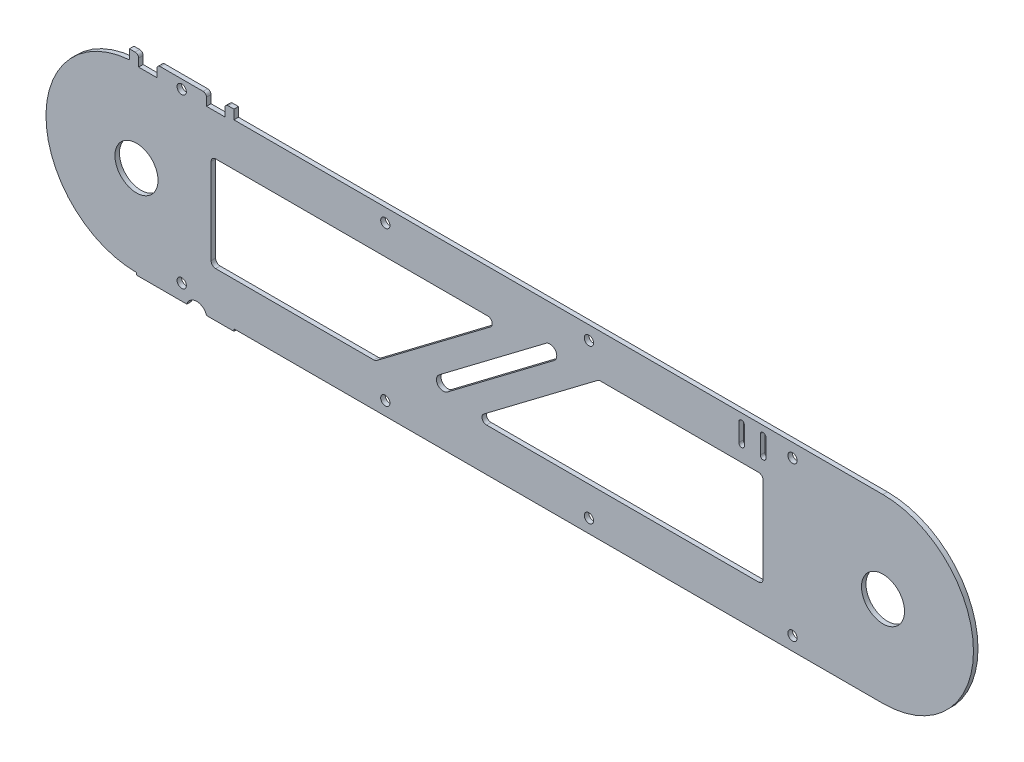
SolidWorks part; units mm, degrees
ref_plane "前视基准面" through (0, 0, 0) normal (0, 0, 1) x (1, 0, 0)
ref_plane "上视基准面" through (0, 0, 0) normal (0, 1, 0) x (1, 0, 0)
ref_plane "右视基准面" through (0, 0, 0) normal (1, 0, 0) x (0, 0, -1)
sketch "草图1" plane through (0, 0, 0) normal (0, 0, 1) x (1, 0, 0)
  line L0 (328.5429, -0.1457) -> (-1.4571, -0.1457) construction
  line L8 (328.5429, -40.1457) -> (-1.4571, -40.1457)
  line L9 (-1.4571, 39.8543) -> (328.5429, 39.8543)
  line L10 (275.5429, 31.8543) -> (266.0429, 31.8543) construction
  line L11 (275.5429, 35.8543) -> (275.5429, 27.8543) construction
  line L12 (276.7929, 35.8543) -> (276.7929, 27.8543)
  line L13 (274.2929, 35.8543) -> (274.2929, 27.8543)
  line L14 (266.0429, 27.8543) -> (266.0429, 35.8543) construction
  line L15 (264.7929, 27.8543) -> (264.7929, 35.8543)
  line L16 (267.2929, 27.8543) -> (267.2929, 35.8543)
  circle A0 centre (-1.4571, -0.1457) radius 9.52
  circle A1 centre (-1.4571, -0.1457) radius 40 construction
  arc A4 (-1.4571, 39.8543) -> (-1.4571, -40.1457) centre (-1.4571, -0.1457) ccw
  circle A11 centre (328.5429, -0.1457) radius 9.52
  circle A12 centre (328.5429, -0.1457) radius 40 construction
  circle A16 centre (328.5429, -0.1457) radius 30 construction
  arc A20 (328.5429, 39.8543) -> (328.5429, -40.1457) centre (328.5429, -0.1457) cw
  arc A21 (276.7929, 35.8543) -> (274.2929, 35.8543) centre (275.5429, 35.8543) ccw
  arc A22 (274.2929, 27.8543) -> (276.7929, 27.8543) centre (275.5429, 27.8543) ccw
  arc A23 (264.7929, 27.8543) -> (267.2929, 27.8543) centre (266.0429, 27.8543) ccw
  arc A24 (267.2929, 35.8543) -> (264.7929, 35.8543) centre (266.0429, 35.8543) ccw
  point P10 (275.5429, 31.8543)
  point P24 (266.0429, 31.8543)
  dimension "D1" = 330
  dimension "D2" = 19.04
  dimension "D3" = 9.5
  dimension "D4" = 19.04
  dimension "D5" = 80
  dimension "D6" = 8
  dimension "D7" = 53
extrude "凸台-拉伸1" add sketch "草图1" along normal blind 2
sketch "草图4" plane through (0, 0, 2) normal (0, 0, 1) x (1, 0, 0)
  line L0 (-1.4571, -40.1457) -> (-1.4571, -41.1257)
  line L1 (328.5429, 39.8543) -> (-1.4571, 39.8543) construction
  line L2 (41.6429, 35.3514) -> (-4.5571, 35.3514)
  line L3 (41.6429, 35.3514) -> (41.6429, 43.9543)
  line L4 (41.6429, 43.9543) -> (-4.5571, 43.9543)
  line L5 (-4.5571, 35.3514) -> (-4.5571, 43.9543)
  line L6 (-1.4571, -41.1257) -> (41.6429, -41.1257)
  line L7 (41.6429, -41.1257) -> (41.6429, -40.1457)
  line L8 (-1.4571, -40.1457) -> (328.5429, -40.1457) construction
  line L9 (41.6429, -40.1457) -> (-1.4571, -40.1457)
  dimension "D1" = 46.2
  dimension "D2" = 3.1
  dimension "D3" = 4.1
  dimension "D4" = 0.98
extrude "凸台-拉伸2" add sketch "草图4" against normal blind 2
sketch "草图2" plane through (0, 0, 2) normal (0, 0, 1) x (1, 0, 0)
  line L0 (198.5429, 33.8543) -> (288.5429, 33.8543) construction
  line L1 (18.5429, 33.8543) -> (198.5429, 33.8543) construction
  line L2 (108.5429, -34.1457) -> (198.5429, 33.8543) construction
  line L3 (18.5429, 33.8543) -> (18.5429, -34.1457) construction
  line L4 (18.5429, -34.1457) -> (108.5429, -34.1457) construction
  line L5 (31.5429, -21.1457) -> (104.1839, -21.1457)
  line L6 (104.1839, -21.1457) -> (159.7721, 20.8543)
  line L7 (31.5429, 20.8543) -> (159.7721, 20.8543)
  line L8 (31.5429, 20.8543) -> (31.5429, -21.1457)
  line L9 (108.5429, -34.1457) -> (288.5429, -34.1457) construction
  line L10 (288.5429, -34.1457) -> (288.5429, 33.8543) construction
  line L12 (275.5429, 20.8543) -> (202.9018, 20.8543)
  line L13 (147.3136, -21.1457) -> (202.9018, 20.8543)
  line L14 (147.3136, -21.1457) -> (275.5429, -21.1457)
  line L15 (275.5429, -21.1457) -> (275.5429, 20.8543)
  line L20 (18.5429, 33.8543) -> (18.5429, 39.8543) construction
  line L28 (288.5429, 33.8543) -> (198.5429, 33.8543) construction
  line L30 (328.5429, 39.8543) -> (41.6429, 39.8543) construction
  line L31 (7.5929, 38.9643) -> (-0.5071, 41.0643) construction
  line L36 (29.4929, 41.0643) -> (37.5929, 41.0643) construction
  line L37 (29.4929, 41.0643) -> (29.4929, 38.9643)
  line L38 (29.4929, 38.9643) -> (37.5929, 38.9643)
  line L39 (37.5929, 41.0643) -> (37.5929, 38.9643)
  line L40 (29.4929, 41.0643) -> (37.5929, 38.9643) construction
  line L41 (29.4929, 38.9643) -> (37.5929, 41.0643) construction
  line L42 (7.5929, 41.0643) -> (-0.5071, 38.9643) construction
  line L43 (18.5429, 33.8543) -> (-161.4571, 33.8543) construction
  line L44 (-0.5071, 41.0643) -> (-0.5071, 38.9643)
  line L45 (7.5929, 38.9643) -> (-0.5071, 38.9643)
  line L46 (7.5929, 41.0643) -> (7.5929, 38.9643)
  line L47 (7.5929, 41.0643) -> (-0.5071, 41.0643) construction
  line L48 (-0.5071, 41.0643) -> (-0.5071, 53.5797)
  line L49 (-0.5071, 53.5797) -> (7.5929, 53.5797)
  line L50 (7.5929, 53.5797) -> (7.5929, 41.0643)
  line L51 (29.4929, 41.0643) -> (29.4929, 53.5797)
  line L52 (29.4929, 53.5797) -> (37.5929, 53.5797)
  line L53 (37.5929, 53.5797) -> (37.5929, 41.0643)
  circle A1 centre (108.5429, 33.8543) radius 2.05
  circle A2 centre (198.5429, 33.8543) radius 2.05
  circle A3 centre (288.5429, 33.8543) radius 2.05
  circle A4 centre (108.5429, -34.1457) radius 2.05
  circle A5 centre (198.5429, -34.1457) radius 2.05
  circle A6 centre (288.5429, -34.1457) radius 2.05
  circle A7 centre (18.5429, -34.1457) radius 2.05
  circle A9 centre (18.5429, 40.0143) radius 2.05
  point P0 (3.5429, 40.0143)
  point P2 (-1.4571, -0.1457)
  point P30 (33.5429, 40.0143)
  dimension "D1" = 8.1
  dimension "D2" = 34
  dimension "D3" = 2.1
  dimension "D8" = 6.16
  dimension "D4" = 15
  dimension "D6" = 13
  dimension "D7" = 13
extrude "切除-拉伸1" cut sketch "草图2" against normal blind 4
sketch "草图3" plane through (0, 0, 2) normal (0, 0, 1) x (1, 0, 0)
  line L0 (202.9018, 20.8543) -> (159.7721, 20.8543) construction
  line L1 (147.3136, -21.1457) -> (104.1839, -21.1457) construction
  line L2 (181.337, 20.8543) -> (125.7487, -21.1457) construction
  line L3 (181.337, 20.8543) -> (134.1674, -14.785) construction
  line L4 (183.1455, 18.4607) -> (135.9759, -17.1786)
  line L5 (179.5285, 23.2479) -> (132.3589, -12.3914)
  arc A0 (183.1455, 18.4607) -> (179.5285, 23.2479) centre (181.337, 20.8543) ccw
  arc A1 (132.3589, -12.3914) -> (135.9759, -17.1786) centre (134.1674, -14.785) ccw
  point P11 (157.7522, 3.0347)
extrude "切除-拉伸2" cut sketch "草图3" against normal blind 10
fillet "圆角1" radius 2 8 edges at (275.5429, -21.1457, 1) (275.5429, 20.8543, 1) (202.9018, 20.8543, 1) (147.3136, -21.1457, 1) (104.1839, -21.1457, 1) (159.7721, 20.8543, 1) (31.5429, -21.1457, 1) (31.5429, 20.8543, 1)
sketch "草图5" plane through (0, 0, 2) normal (0, 0, 1) x (1, 0, 0)
  line L0 (-1.4571, -41.1257) -> (41.6429, -41.1257) construction
  line L1 (20.8062, -41.1257) -> (29.5079, -41.1257)
  arc A0 (20.8062, -41.1257) -> (29.5079, -41.1257) centre (25.157, -42.4207) cw
extrude "切除-拉伸3" cut sketch "草图5" against normal blind 2
fillet "圆角2" radius 1.5 4 edges at (37.5929, 43.9543, 1) (29.4929, 43.9543, 1) (7.5929, 43.9543, 1) (-0.5071, 43.9543, 1)
sketch "草图6" plane through (0, 0, 0) normal (0, 0, -1) x (-1, 0, 0)
  line L0 (-275.5429, 35.8543) -> (-275.5429, 27.8543)
  line L1 (-266.0429, 35.8543) -> (-266.0429, 27.8543)
